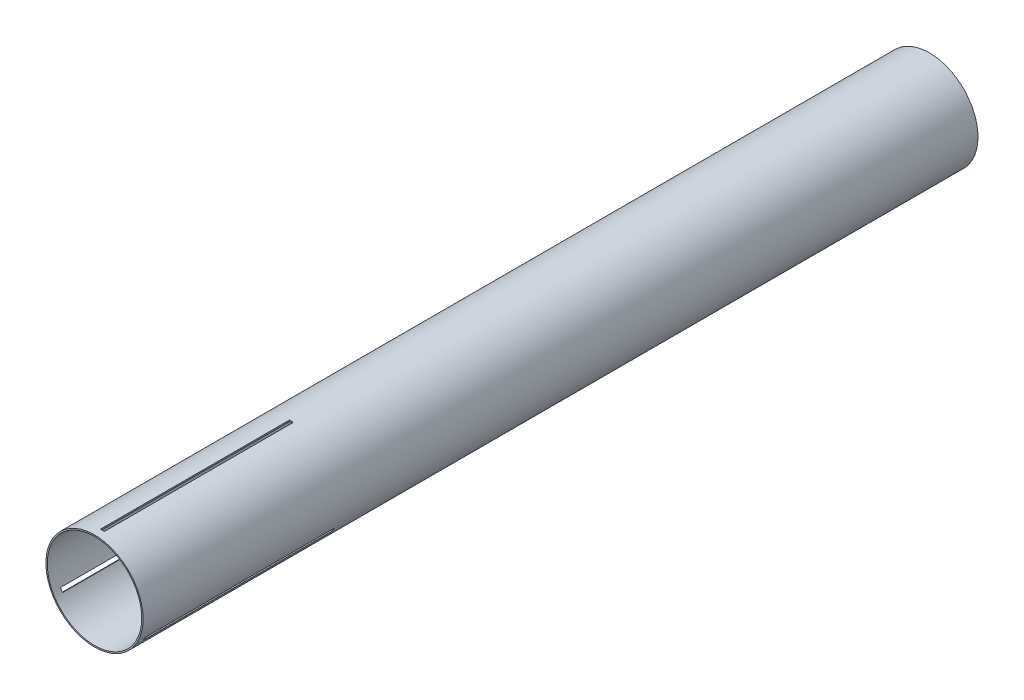
SolidWorks part; units mm, degrees
ref_plane "Plan de face" through (0, 0, 0) normal (0, 0, 1) x (1, 0, 0)
ref_plane "Plan de dessus" through (0, 0, 0) normal (0, 1, 0) x (1, 0, 0)
ref_plane "Plan de droite" through (0, 0, 0) normal (1, 0, 0) x (0, 0, -1)
sketch "Esquisse2" plane through (0, 0, 0) normal (0, 0, 1) x (1, 0, 0)
  circle A0 centre (0, 0) radius 78.359
  circle A1 centre (0, 0) radius 76.2
  dimension "D1" = 156.718
  dimension "D2" = 152.4
extrude "Boss.-Extru.1" add sketch "Esquisse2" along normal blind 1346.2
sketch "Esquisse3" plane through (0, 0, 0) normal (0, 1, 0) x (1, 0, 0)
  line L0 (0, -1346.2) -> (0, -1333.5)
  line L1 (-78.359, -1346.2) -> (78.359, -1346.2) construction
  line L2 (0, -1333.5) -> (0, -1181.1)
  line L3 (0, -1333.5) -> (-3.175, -1333.5)
  line L5 (3.175, -1028.7) -> (-3.175, -1028.7)
  line L6 (3.175, -1028.7) -> (3.175, -1333.5)
  line L7 (3.175, -1333.5) -> (-3.175, -1333.5)
  line L8 (-3.175, -1028.7) -> (-3.175, -1333.5)
  line L9 (3.175, -1028.7) -> (-3.175, -1333.5) construction
  line L10 (3.175, -1333.5) -> (-3.175, -1028.7) construction
  dimension "D1" = 12.7
  dimension "D2" = 152.4
  dimension "D3" = 3.175
extrude "Enlèv. mat.-Extru.1" cut sketch "Esquisse3" along normal blind 152.4 contours L7 L6 L5 L8
pattern_circular "Répétition circulaire1" count 3 every 120 about axis through (0, 0, 0) along (0, 0, 1) of "Enlèv. mat.-Extru.1"
